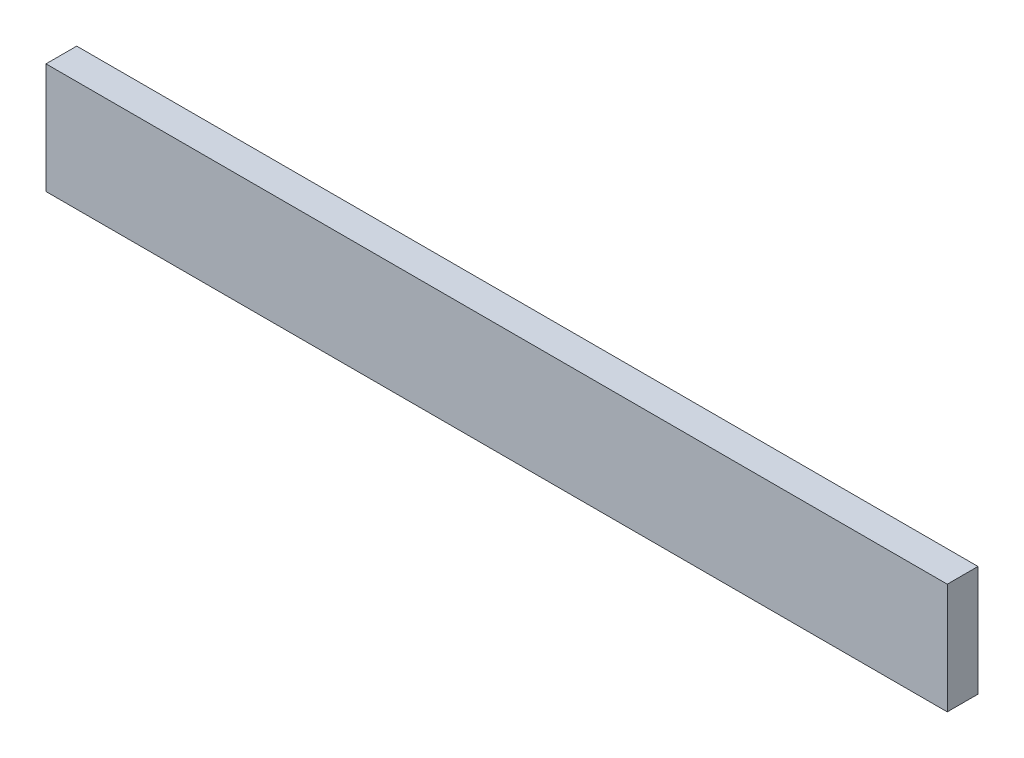
SolidWorks part; units mm, degrees
ref_plane "Plan de face" through (0, 0, 0) normal (0, 0, 1) x (1, 0, 0)
ref_plane "Plan de dessus" through (0, 0, 0) normal (0, 1, 0) x (1, 0, 0)
ref_plane "Plan de droite" through (0, 0, 0) normal (1, 0, 0) x (0, 0, -1)
sketch "Esquisse1" plane through (0, 0, 0) normal (0, 0, 1) x (1, 0, 0)
  line L1 (0, 0) -> (440, 0)
  line L2 (0, 0) -> (0, 54)
  line L3 (0, 54) -> (440, 54)
  line L4 (440, 0) -> (440, 54)
  dimension "D1" = 440
  dimension "D2" = 54
extrude "Boss.-Extru.1" add sketch "Esquisse1" along normal blind 15
